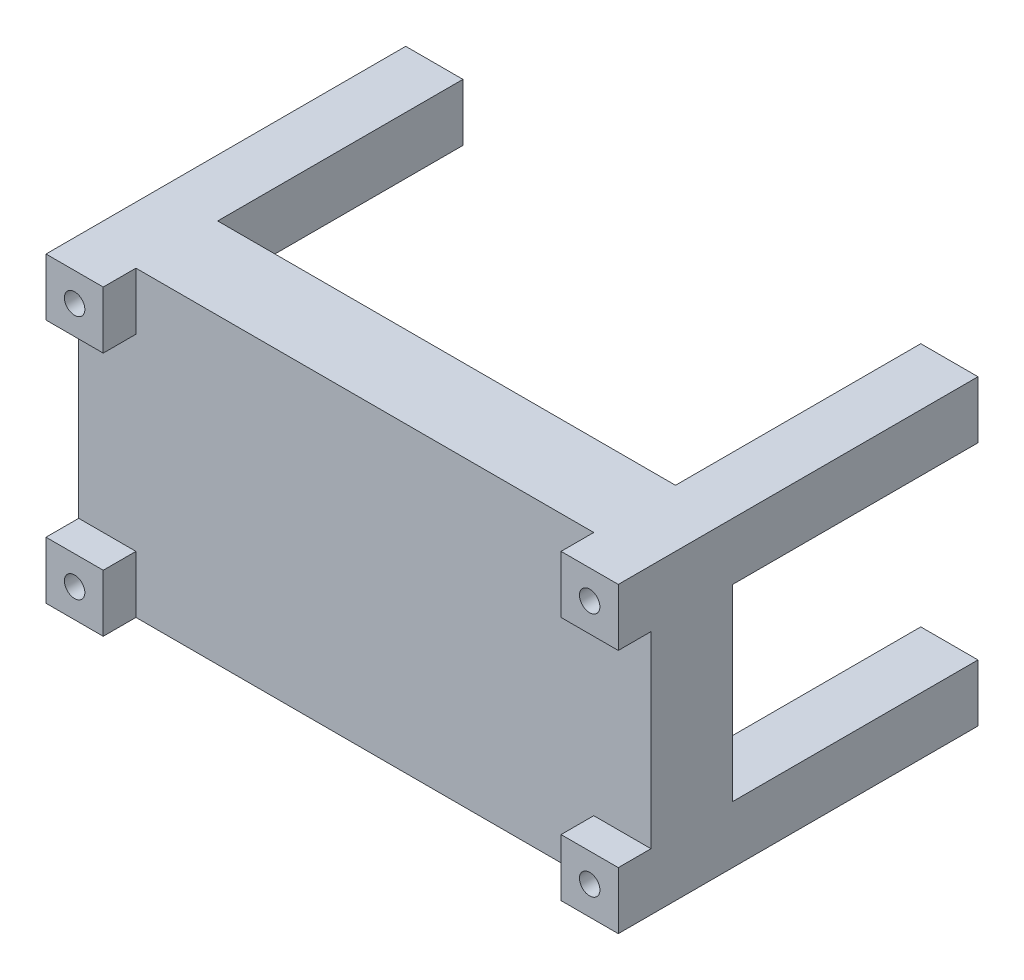
SolidWorks part; units mm, degrees
ref_plane "Front Plane" through (0, 0, 0) normal (0, 0, 1) x (1, 0, 0)
ref_plane "Top Plane" through (0, 0, 0) normal (0, 1, 0) x (1, 0, 0)
ref_plane "Right Plane" through (0, 0, 0) normal (1, 0, 0) x (0, 0, -1)
sketch "Sketch1" plane through (0, 0, 0) normal (0, 0, 1) x (1, 0, 0)
  line L1 (0, 0) -> (70, 0)
  line L2 (0, 0) -> (0, 37)
  line L3 (0, 37) -> (70, 37)
  line L4 (70, 0) -> (70, 37)
  dimension "D1" = 37
  dimension "D2" = 70
extrude "Boss-Extrude1" add sketch "Sketch1" along normal blind 10
sketch "Sketch2" plane through (0, 0, 0) normal (0, 0, 1) x (1, 0, 0)
  line L0 (0, 30) -> (7, 37) construction
  line L1 (0, 37) -> (7, 37)
  line L2 (0, 37) -> (0, 30)
  line L3 (0, 30) -> (7, 30)
  line L4 (7, 37) -> (7, 30)
  line L5 (70, 37) -> (63, 37)
  line L6 (70, 37) -> (70, 30)
  line L7 (70, 30) -> (63, 30)
  line L8 (63, 37) -> (63, 30)
  line L9 (70, 0) -> (63, 0)
  line L10 (70, 0) -> (70, 7)
  line L11 (70, 7) -> (63, 7)
  line L12 (63, 0) -> (63, 7)
  line L13 (0, 0) -> (7, 0)
  line L14 (0, 0) -> (0, 7)
  line L15 (0, 7) -> (7, 7)
  line L16 (7, 0) -> (7, 7)
  line L17 (7, 30) -> (0, 37) construction
  line L18 (0, 0) -> (7, 7) construction
  line L19 (7, 0) -> (0, 7) construction
  line L20 (0, 0) -> (63, 0) construction
  line L21 (70, 7) -> (63, 0) construction
  line L22 (63, 7) -> (70, 0) construction
  line L23 (70, 30) -> (63, 37) construction
  line L24 (63, 30) -> (70, 37) construction
  circle A0 centre (3.5, 33.5) radius 1.25
  circle A1 centre (3.5, 3.5) radius 1.25
  circle A2 centre (66.5, 3.5) radius 1.25
  circle A3 centre (66.5, 33.5) radius 1.25
  dimension "D9" = 2.5
  dimension "D10" = 2.5
  dimension "D11" = 2.5
  dimension "D12" = 2.5
  dimension "D1" = 7
  dimension "D2" = 7
  dimension "D3" = 7
  dimension "D4" = 7
  dimension "D5" = 7
  dimension "D6" = 7
  dimension "D7" = 7
  dimension "D8" = 7
extrude "Boss-Extrude4" add sketch "Sketch2" along normal blind 14 and the other way blind 30
